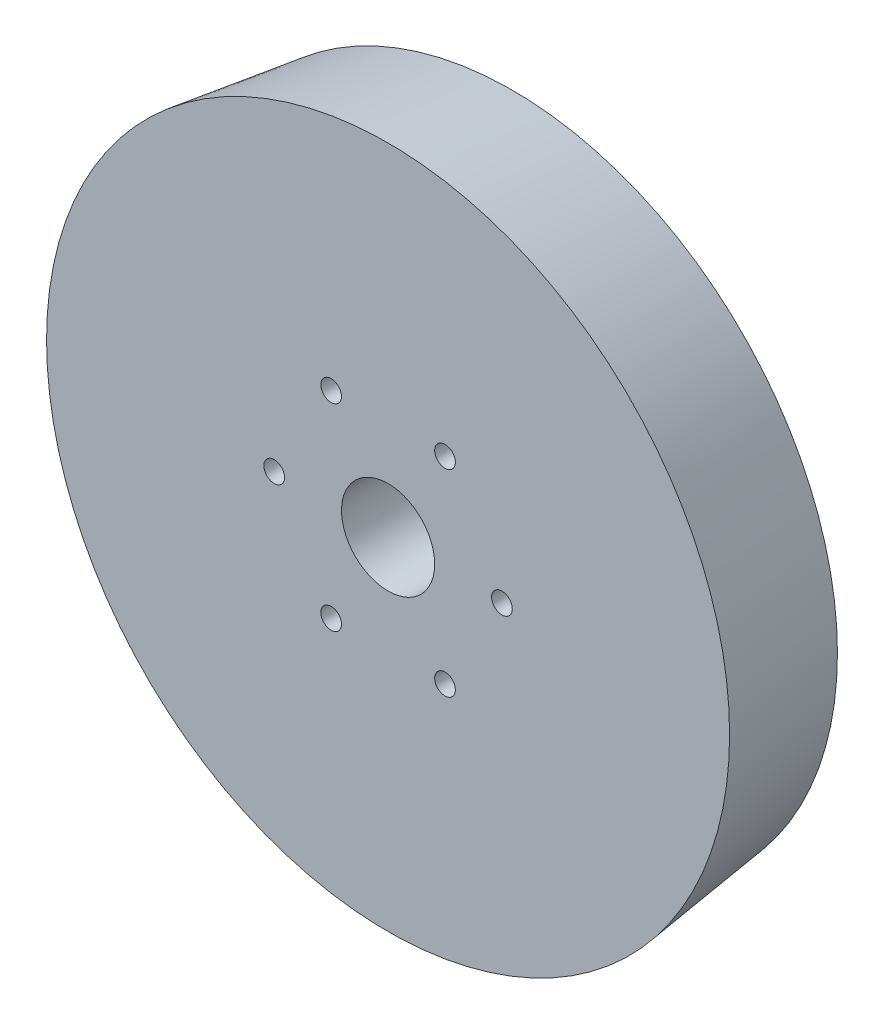
SolidWorks part; units mm, degrees
ref_plane "Front" through (0, 0, 0) normal (0, 0, 1) x (1, 0, 0)
ref_plane "Top" through (0, 0, 0) normal (0, 1, 0) x (1, 0, 0)
ref_plane "Right" through (0, 0, 0) normal (1, 0, 0) x (0, 0, -1)
sketch "Sketch1" plane through (0, 0, 0) normal (0, 0, 1) x (1, 0, 0)
  circle A0 centre (0, 0) radius 104.775
  dimension "D1" = 209.55
extrude "Boss-Extrude1" add sketch "Sketch1" against normal blind 38.1 draft 7.5
sketch "Sketch2" plane through (0, 0, 0) normal (0, 0, 1) x (1, 0, 0)
  circle A0 centre (0, 0) radius 14.2875
  dimension "D1" = 28.575
extrude "Cut-Extrude1" cut sketch "Sketch2" against normal through all
sketch "Sketch3" plane through (0, 0, 0) normal (0, 0, 1) x (1, 0, 0)
  circle A0 centre (0, 0) radius 34.925 construction
  circle A1 centre (34.925, 0) radius 3.175
  circle A2 centre (17.4625, -30.2459) radius 3.175
  circle A3 centre (-17.4625, -30.2459) radius 3.175
  circle A4 centre (-34.925, 0) radius 3.175
  circle A5 centre (-17.4625, 30.2459) radius 3.175
  circle A6 centre (17.4625, 30.2459) radius 3.175
  point P17 (0, 0)
  dimension "D1" = 69.85
  dimension "D2" = 6.35
  dimension "D3" = 6
extrude "Cut-Extrude2" cut sketch "Sketch3" against normal blind 38.1
